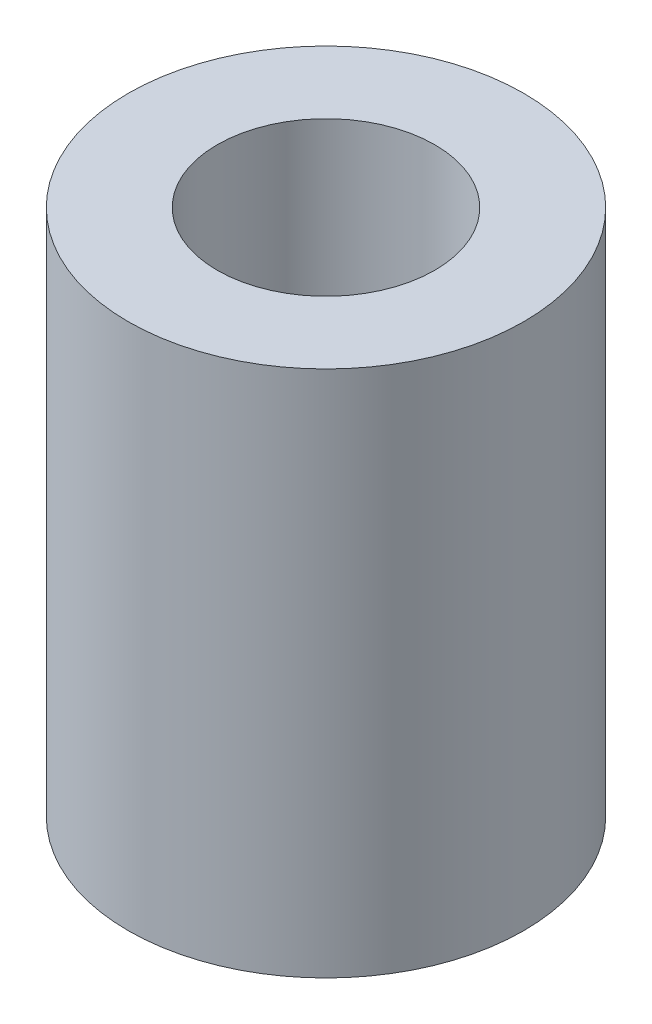
SolidWorks part; units mm, degrees
ref_plane "Front Plane" through (0, 0, 0) normal (0, 0, 1) x (1, 0, 0)
ref_plane "Top Plane" through (0, 0, 0) normal (0, 1, 0) x (1, 0, 0)
ref_plane "Right Plane" through (0, 0, 0) normal (1, 0, 0) x (0, 0, -1)
sketch "Sketch1" plane through (0, 0, 0) normal (0, 1, 0) x (1, 0, 0)
  circle A0 centre (0, 0) radius 1.65
  circle A1 centre (0, 0) radius 3
  dimension "D1" = 3.3
  dimension "D2" = 6
extrude "Boss-Extrude1" add sketch "Sketch1" along normal blind 8
